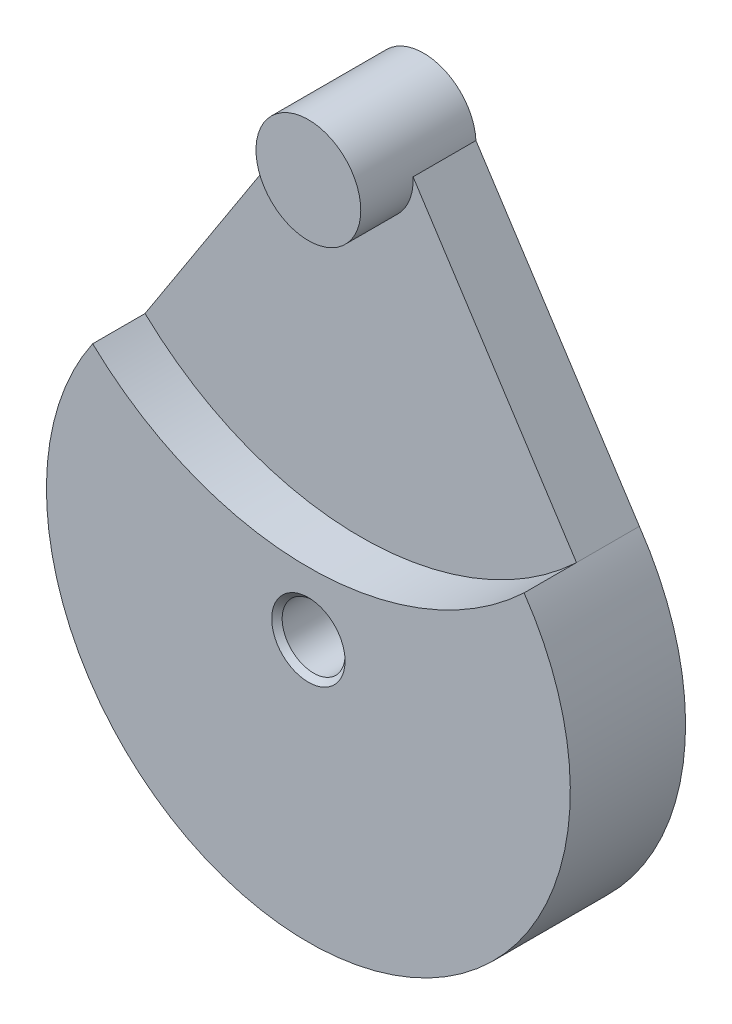
SolidWorks part; units mm, degrees
ref_plane "Ön Düzlem" through (0, 0, 0) normal (0, 0, 1) x (1, 0, 0)
ref_plane "Üst Düzlem" through (0, 0, 0) normal (0, 1, 0) x (1, 0, 0)
ref_plane "Sağ Düzlem" through (0, 0, 0) normal (1, 0, 0) x (0, 0, -1)
sketch "Sketch1" plane through (0, 0, 0) normal (0, 0, 1) x (1, 0, 0)
  circle A0 centre (0, 0) radius 50
  dimension "D1" = 100
extrude "Boss-Extrude1" add sketch "Sketch1" along normal blind 6
sketch "Sketch2" plane through (0, 0, 6) normal (0, 0, 1) x (1, 0, 0)
  line L0 (0, -69.7394) -> (0, 89.119) construction
  line L1 (-85.1612, 0) -> (85.98, 0) construction
  circle A0 centre (0, 38) radius 5
  arc A1 (-20.5891, 14.1806) -> (20.5891, 14.1806) centre (0, 0) ccw
  arc A2 (-20.5891, 14.1806) -> (20.5891, 14.1806) centre (0, 36) ccw
  dimension "D1" = 10
  dimension "D3" = 50
  dimension "D4" = 60
  dimension "D2" = 38
  dimension "D5" = 36
extrude "Boss-Extrude2" add sketch "Sketch2" along normal blind 5
sketch "Sketch3" plane through (0, 0, 11) normal (0, 0, 1) x (1, 0, 0)
  circle A0 centre (0, 0) radius 3
  dimension "D1" = 6
extrude "Cut-Extrude1" cut sketch "Sketch3" against normal through all
sketch "Sketch4" plane through (0, 0, 6) normal (0, 0, 1) x (1, 0, 0)
  line L0 (-20.5891, 14.1806) -> (-2.288, 42.4458)
  line L1 (20.5891, 14.1806) -> (2.288, 42.4458)
  line L2 (2.288, 42.4458) -> (20.5891, 14.1806)
  circle A0 centre (0, 38) radius 5 construction
  circle A1 centre (0, 0) radius 50
  circle A2 centre (0, 0) radius 50
  circle A3 centre (0, 38) radius 5 construction
  arc M2 (20.5891, 14.1806) -> (-20.5891, 14.1806) centre (0, 0) cw
  circle M4 centre (0, 38) radius 5
  circle M5 centre (0, 0) radius 50
  dimension "D1" = 0
extrude "Cut-Extrude2" cut sketch "Sketch4" against normal blind 31 and the other way through all contours L1 L0 M5 M2 M4
chamfer "Chamfer1" distance 0.5 angle 45 2 edges at (3, 0, 0) (3, 0, 11)
